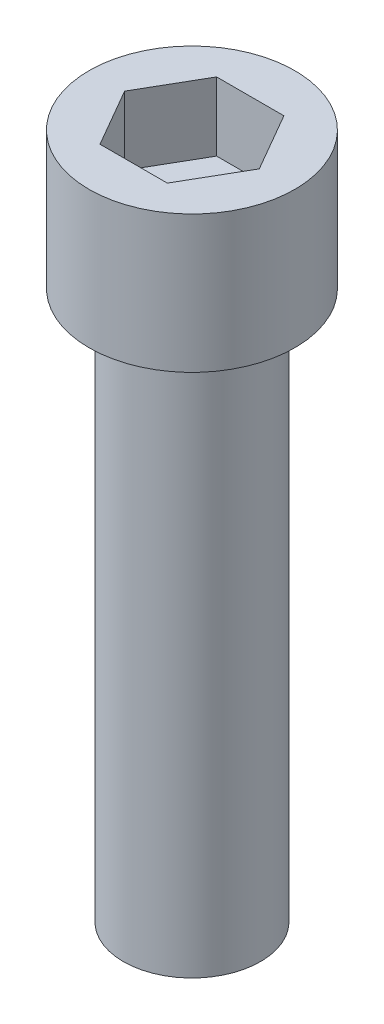
SolidWorks part; units mm, degrees
material "AISI 304"
ref_plane "Front Plane" through (0, 0, 0) normal (0, 0, 1) x (1, 0, 0)
ref_plane "Top Plane" through (0, 0, 0) normal (0, 1, 0) x (1, 0, 0)
ref_plane "Right Plane" through (0, 0, 0) normal (1, 0, 0) x (0, 0, -1)
sketch "Sketch1" plane through (0, 0, 0) normal (0, 0, 1) x (1, 0, 0)
  line L0 (0, 61.6916) -> (0, -59.3578) construction
  line L1 (0, -80) -> (10, -80)
  line L2 (10, -80) -> (10, 0)
  line L3 (10, 0) -> (15, 0)
  line L4 (15, 0) -> (15, 20)
  line L5 (15, 20) -> (0, 20)
  line L6 (0, 20) -> (0, -80)
  dimension "D1" = 80
  dimension "D2" = 30
  dimension "D3" = 20
  dimension "D4" = 20
revolve "Revolve1" add sketch "Sketch1" angle 360 about L0
sketch "Sketch2" plane through (0, 20, 0) normal (0, 1, 0) x (-1, 0, 0)
  line L1 (-4.9075, -8.5) -> (4.9075, -8.5)
  line L2 (4.9075, -8.5) -> (9.815, 0)
  line L3 (9.815, 0) -> (4.9075, 8.5)
  line L4 (4.9075, 8.5) -> (-4.9075, 8.5)
  line L5 (-4.9075, 8.5) -> (-9.815, 0)
  line L6 (-9.815, 0) -> (-4.9075, -8.5)
  circle A0 centre (0, 0) radius 8.5 construction
  dimension "D1" = 17
extrude "Cut-Extrude1" cut sketch "Sketch2" against normal blind 10
